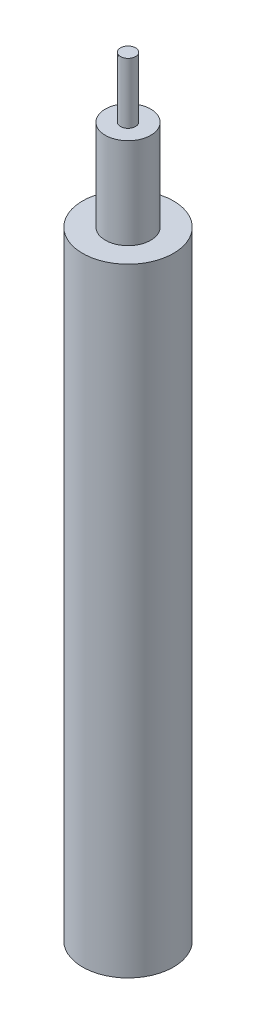
SolidWorks part; units mm, degrees
ref_plane "Front Plane" through (0, 0, 0) normal (0, 0, 1) x (1, 0, 0)
ref_plane "Top Plane" through (0, 0, 0) normal (0, 1, 0) x (1, 0, 0)
ref_plane "Right Plane" through (0, 0, 0) normal (1, 0, 0) x (0, 0, -1)
sketch "Sketch1" plane through (0, 0, 0) normal (0, 1, 0) x (1, 0, 0)
  circle A0 centre (0, 0) radius 2.3813
  dimension "D1" = 4.7625
extrude "Boss-Extrude1" add sketch "Sketch1" against normal blind 9.525
sketch "Sketch2" plane through (0, -9.525, 0) normal (0, -1, 0) x (-1, 0, 0)
  circle A0 centre (0, 0) radius 4.7625
  dimension "D1" = 9.525
extrude "Boss-Extrude2" add sketch "Sketch2" along normal blind 64.77
sketch "Sketch3" plane through (0, 0, 0) normal (0, 1, 0) x (1, 0, 0)
  circle A0 centre (0, 0) radius 0.7937
extrude "Boss-Extrude3" add sketch "Sketch3" along normal blind 6.35
